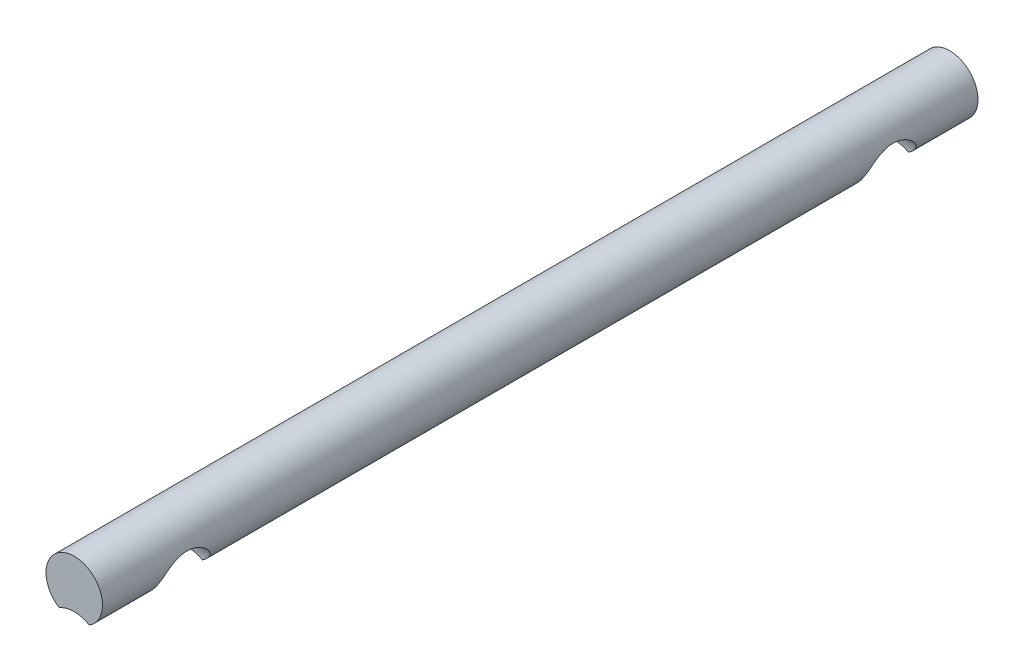
SolidWorks part; units mm, degrees
ref_plane "Спереди" through (0, 0, 0) normal (0, 0, 1) x (1, 0, 0)
ref_plane "Сверху" through (0, 0, 0) normal (0, 1, 0) x (1, 0, 0)
ref_plane "Справа" through (0, 0, 0) normal (1, 0, 0) x (0, 0, -1)
sketch "Эскиз1" plane through (0, 0, 0) normal (0, 0, 1) x (1, 0, 0)
  line L0 (0, 100) -> (0, -70) construction
  circle A0 centre (0, 0) radius 100
  circle A2 centre (0, -175) radius 105
  dimension "D1" = 200
  dimension "D2" = 210
  dimension "D3" = 170
extrude "Бобышка-Вытянуть1" add sketch "Эскиз1" along normal mid plane 3100 contours A0 L0 A2 | L0 A0 A2
sketch "Эскиз2" plane through (0, 0, 0) normal (1, 0, 0) x (0, 0, -1)
  line L0 (-1550, 100) -> (-1550, -84.5714) construction
  line L1 (-1550, -84.5714) -> (1550, -84.5714) construction
  line L2 (0, 0) -> (0, 114.413) construction
  circle A0 centre (-1250, -84.5714) radius 100
  circle A1 centre (1250, -84.5714) radius 100
  dimension "D2" = 200
  dimension "D1" = 300
extrude "Вырез-Вытянуть1" cut sketch "Эскиз2" against normal mid plane 6000
sketch "Эскиз3" plane through (0, 0, 0) normal (0, 1, 0) x (1, 0, 0)
  line L0 (-100, -1550) -> (100, -1550) construction
  line L1 (0, -1170.923) -> (0, -1329.077) construction
  line L2 (-79.077, -1250) -> (79.077, -1250) construction
  line L3 (0, 0) -> (163.9977, 0) construction
  line L4 (-79.077, 1250) -> (79.077, 1250) construction
  line L5 (0, 1170.923) -> (0, 1329.077) construction
  circle A0 centre (0, -1250) radius 79.077 construction
  circle A1 centre (0, 1250) radius 79.077 construction
  dimension "D2" = 158.1541
  dimension "D1" = 300
equation "\"Длина\"= 2500 + 600"
equation "\"D1@Бобышка-Вытянуть1\"=\"Длина\""
